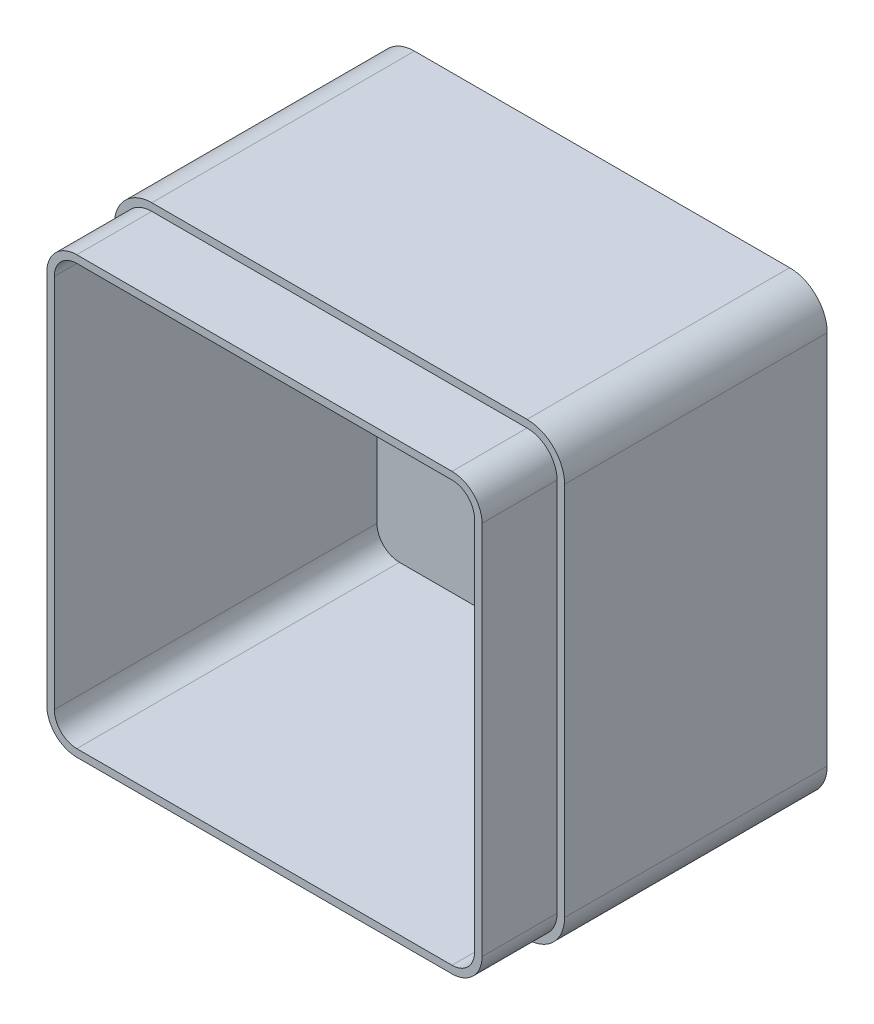
SolidWorks part; units mm, degrees
ref_plane "Front" through (0, 0, 0) normal (0, 0, 1) x (1, 0, 0)
ref_plane "Top" through (0, 0, 0) normal (0, 1, 0) x (1, 0, 0)
ref_plane "Right" through (0, 0, 0) normal (1, 0, 0) x (0, 0, -1)
sketch "Sketch1" plane through (0, 0, 0) normal (0, 0, 1) x (1, 0, 0)
  line L1 (0, 0) -> (120, 0)
  line L2 (0, 0) -> (0, -120)
  line L3 (0, -120) -> (120, -120)
  line L4 (120, 0) -> (120, -120)
  dimension "D1" = 120
  dimension "D2" = 120
extrude "Boss-Extrude1" add sketch "Sketch1" along normal blind 90
fillet "Fillet1" radius 10 4 edges at (0, -120, 45) (120, -120, 45) (120, 0, 45) (0, 0, 45)
shell "Shell1" thickness 4
sketch "Sketch2" plane through (0, 0, 90) normal (0, 0, 1) x (1, 0, 0)
  line L0 (2, -10) -> (2, -110)
  line L1 (10, -118) -> (110, -118)
  line L2 (118, -110) -> (118, -10)
  line L3 (110, -2) -> (10, -2)
  line L4 (0, -10) -> (0, -110)
  line L5 (10, -120) -> (110, -120)
  line L6 (120, -110) -> (120, -10)
  line L7 (110, 0) -> (10, 0)
  line L8 (0, -10) -> (0, -110)
  line L9 (10, -120) -> (110, -120)
  line L10 (120, -110) -> (120, -10)
  line L11 (110, 0) -> (10, 0)
  arc A0 (2, -110) -> (10, -118) centre (10, -110) ccw
  arc A1 (110, -118) -> (118, -110) centre (110, -110) ccw
  arc A2 (118, -10) -> (110, -2) centre (110, -10) ccw
  arc A3 (10, -2) -> (2, -10) centre (10, -10) ccw
  arc A4 (0, -110) -> (10, -120) centre (10, -110) ccw
  arc A5 (110, -120) -> (120, -110) centre (110, -110) ccw
  arc A6 (120, -10) -> (110, 0) centre (110, -10) ccw
  arc A7 (10, 0) -> (0, -10) centre (10, -10) ccw
  arc A8 (0, -110) -> (10, -120) centre (10, -110) ccw
  arc A9 (110, -120) -> (120, -110) centre (110, -110) ccw
  arc A10 (120, -10) -> (110, 0) centre (110, -10) ccw
  arc A11 (10, 0) -> (0, -10) centre (10, -10) ccw
  dimension "D1" = 0
  dimension "D2" = 2
extrude "Cut-Extrude2" cut sketch "Sketch2" against normal blind 20 contours L3 A3 L0 A0 L1 A1 L2 A2
